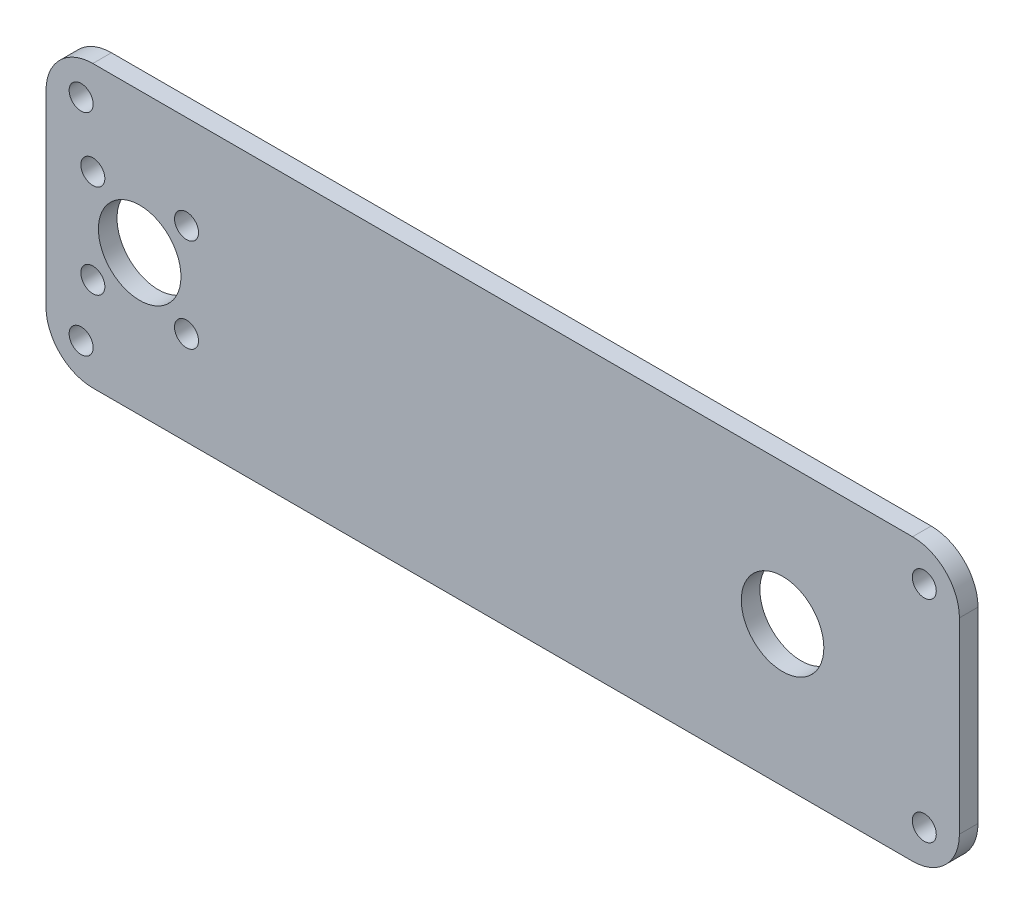
SolidWorks part; units mm, degrees
ref_plane "Front Plane" through (0, 0, 0) normal (0, 0, 1) x (1, 0, 0)
ref_plane "Top Plane" through (0, 0, 0) normal (0, 1, 0) x (1, 0, 0)
ref_plane "Right Plane" through (0, 0, 0) normal (1, 0, 0) x (0, 0, -1)
sketch "Sketch2" plane through (0, 0, 0) normal (0, 0, 1) x (1, 0, 0)
  line L0 (0, 0) -> (0, -72030.4166) construction
  line L1 (78, 24) -> (-78, 24)
  line L2 (78, 24) -> (78, -24)
  line L3 (78, -24) -> (-78, -24)
  line L4 (-78, 24) -> (-78, -24)
  line L5 (78, 24) -> (-78, -24) construction
  line L6 (78, -24) -> (-78, 24) construction
  line L7 (0, 0) -> (72030.4166, 0) construction
  line L9 (-46, 20) -> (17, 20) construction
  line L10 (-46, 20) -> (-46, -20) construction
  line L11 (-46, -20) -> (17, -20) construction
  line L12 (17, 20) -> (17, -20) construction
  line L13 (-46, 20) -> (17, -20) construction
  line L14 (-46, -20) -> (17, 20) construction
  line L15 (-70, 8) -> (-54, 8) construction
  line L16 (-70, 8) -> (-70, -8) construction
  line L17 (-70, -8) -> (-54, -8) construction
  line L18 (-54, 8) -> (-54, -8) construction
  line L19 (-70, 8) -> (-54, -8) construction
  line L20 (-70, -8) -> (-54, 8) construction
  line L21 (10.5, -16) -> (-39.5, -16) construction
  line L22 (10.5, -16) -> (10.5, 16) construction
  line L23 (10.5, 16) -> (-39.5, 16) construction
  line L24 (-39.5, -16) -> (-39.5, 16) construction
  line L25 (10.5, -16) -> (-39.5, 16) construction
  line L26 (10.5, 16) -> (-39.5, -16) construction
  line L31 (7.35, -12) -> (-36.35, -12) construction
  line L32 (7.35, -12) -> (7.35, -8) construction
  line L33 (-50, -12) -> (-74, -12) construction
  line L34 (-50, -12) -> (-50, 12) construction
  line L35 (-50, 12) -> (-74, 12) construction
  line L36 (-74, -12) -> (-74, 12) construction
  line L37 (-50, -12) -> (-74, 12) construction
  line L38 (-50, 12) -> (-74, -12) construction
  line L39 (7.35, 12) -> (-36.35, 12) construction
  line L40 (-36.35, -12) -> (-36.35, -8) construction
  line L41 (7.35, -12) -> (-36.35, 12) construction
  line L42 (7.35, 12) -> (-36.35, -12) construction
  line L44 (-4.7, 19.1) -> (47.7956, 19.1) construction
  line L45 (5.35, -10) -> (-34.35, -10) construction
  line L46 (5.35, -10) -> (5.35, 10) construction
  line L47 (5.35, 10) -> (-34.35, 10) construction
  line L48 (-34.35, -10) -> (-34.35, 10) construction
  line L49 (5.35, -10) -> (-34.35, 10)
  line L50 (5.35, 10) -> (-34.35, -10)
  line L51 (-4.7, -19.1) -> (47.7956, -19.1) construction
  line L52 (-36.35, 8) -> (-42, 8) construction
  line L53 (13, -8) -> (7.35, -8) construction
  line L54 (13, -8) -> (13, 8) construction
  line L55 (13, 8) -> (7.35, 8) construction
  line L56 (-42, -8) -> (-42, 8) construction
  line L57 (13, -8) -> (-42, 8) construction
  line L58 (13, 8) -> (-42, -8) construction
  line L59 (-36.35, -8) -> (-42, -8) construction
  line L60 (-36.35, 8) -> (-36.35, 12) construction
  line L61 (7.35, 8) -> (7.35, 12) construction
  line L64 (9.0311, 16) -> (-48518.2868, 16) construction
  line L65 (10.5, 18.05) -> (13.5, 18.05) construction
  line L66 (10.5, 13.95) -> (13.5, 13.95) construction
  line L67 (-21.5, 13.95) -> (-18.5, 13.95) construction
  line L68 (-21.5, 18.05) -> (-18.5, 18.05) construction
  line L69 (10.5, 13.95) -> (-21.5, 13.95) construction
  line L70 (-21.5, -18.05) -> (-18.5, -18.05) construction
  line L71 (-21.5, -13.95) -> (-18.5, -13.95) construction
  line L72 (10.5, -18.05) -> (13.5, -18.05) construction
  line L73 (10.5, -13.95) -> (13.5, -13.95) construction
  line L75 (72, -18) -> (-72, -18) construction
  line L76 (72, -18) -> (72, 18) construction
  line L77 (72, 18) -> (-72, 18) construction
  line L78 (-72, -18) -> (-72, 18) construction
  line L79 (72, -18) -> (-72, 18) construction
  line L80 (72, 18) -> (-72, -18) construction
  circle A0 centre (-70, 8) radius 2.05
  circle A1 centre (-54, 8) radius 2.05
  circle A2 centre (-54, -8) radius 2.05
  circle A3 centre (-70, -8) radius 2.05
  arc A6 (10.5, 18.05) -> (10.5, 13.95) centre (10.5, 16) ccw construction
  circle A7 centre (-39.5, 16) radius 2.05 construction
  circle A8 centre (-39.5, -16) radius 2.05 construction
  circle A9 centre (-4.7, 0) radius 19.1 construction
  arc A12 (-4.7, 19.1) -> (-4.7, -19.1) centre (-4.7, 0) ccw construction
  circle A13 centre (47.7956, 0) radius 19.1 construction
  arc A14 (47.7956, -19.1) -> (47.7956, 19.1) centre (47.7956, 0) ccw construction
  arc A15 (-4.7, 19.1) -> (-4.7, -19.1) centre (-4.7, 0) ccw construction
  circle A16 centre (47.7956, 0) radius 7.05
  arc A18 (13.5, 13.95) -> (13.5, 18.05) centre (13.5, 16) ccw construction
  arc A19 (-18.5, 13.95) -> (-18.5, 18.05) centre (-18.5, 16) ccw construction
  arc A20 (-21.5, 18.05) -> (-21.5, 13.95) centre (-21.5, 16) ccw construction
  arc A21 (-21.5, -18.05) -> (-21.5, -13.95) centre (-21.5, -16) cw construction
  arc A22 (-18.5, -13.95) -> (-18.5, -18.05) centre (-18.5, -16) cw construction
  arc A23 (10.5, -18.05) -> (10.5, -13.95) centre (10.5, -16) cw construction
  arc A24 (13.5, -13.95) -> (13.5, -18.05) centre (13.5, -16) cw construction
  circle A25 centre (-62, 0) radius 7.05
  circle A26 centre (72, 18) radius 2.05
  circle A27 centre (72, -18) radius 2.05
  circle A28 centre (-72, -18) radius 2.05
  circle A29 centre (-72, 18) radius 2.05
  point P0 (0, 0)
  point P10 (-14.5, 0)
  point P15 (-62, 0)
  point P20 (-14.5, 0)
  point P25 (-14.5, 0)
  point P30 (-62, 0)
  point P39 (-14.5, 0)
  point P47 (-14.5, 0)
  point P52 (-14.5, 0)
  point P95 (0, 0)
  dimension "D7" = 4.1
  dimension "D14" = 38.2
  dimension "D21" = 14.1
  dimension "D1" = 156
  dimension "D2" = 48
  dimension "D3" = 63
  dimension "D4" = 40
  dimension "D5" = 50
  dimension "D6" = 32
  dimension "D8" = 16
  dimension "D9" = 16
  dimension "D10" = 24
  dimension "D11" = 24
  dimension "D12" = 43.7
  dimension "D13" = 24
  dimension "D16" = 39.7
  dimension "D17" = 20
  dimension "D18" = 10.05
  dimension "D19" = 4
  dimension "D20" = 8
  dimension "D22" = 55
  dimension "D23" = 16
  dimension "D24" = 3
  dimension "D26" = 32
  dimension "D27" = 144
  dimension "D28" = 36
  dimension "D25" = 2
extrude "Boss-Extrude2" add sketch "Sketch2" along normal blind 3.175
fillet "Fillet1" radius 8 4 edges at (78, -24, 1.5875) (78, 24, 1.5875) (-78, -24, 1.5875) (-78, 24, 1.5875)
equation "\"w\"= 156mm"
equation "\"h\"= 48mm"
equation "\"servoheight\"= 40mm"
equation "\"servowidth\"= 63mm"
equation "\"servowidthholes\"= 50mm"
equation "\"servoheightholes\"= 32mm"
equation "\"sh\"= 4.1mm"
equation "\"clampHoleSquare\"= 16mm"
equation "\"clampSquare\"= 24mm"
equation "\"D1@Sketch2\"=\"w\""
equation "\"D2@Sketch2\"=\"h\""
equation "\"D3@Sketch2\"=\"servowidth\""
equation "\"D4@Sketch2\"=\"servoheight\""
equation "\"D5@Sketch2\"=\"servowidthholes\""
equation "\"D6@Sketch2\"=\"servoheightholes\""
equation "\"D8@Sketch2\"=\"clampHoleSquare\""
equation "\"D9@Sketch2\"=\"clampHoleSquare\""
equation "\"D10@Sketch2\"=\"clampSquare\""
equation "\"D11@Sketch2\"=\"clampSquare\""
equation "\"D7@Sketch2\"=\"sh\""
equation "\"servoh\"= 20mm"
equation "\"servow\"= 39.7mm"
equation "\"D12@Sketch2\"=\"servow\"+4"
equation "\"D13@Sketch2\"=\"servoh\" +4"
equation "\"pitchDiameter\"= 38.2mm"
equation "\"D14@Sketch2\"=\"pitchDiameter\""
equation "\"D16@Sketch2\"=\"servow\""
equation "\"D17@Sketch2\"=\"servoh\""
equation "\"D18@Sketch2\"=10.05mm"
equation "\"pathLength\"= 225mm"
equation "\"D15@Sketch2\"=\"pathLength\""
equation "\"bearingOD\"= 14.1mm"
equation "\"D21@Sketch2\"=\"bearingOD\""
equation "\"thick\"= 3.175mm"
equation "\"D1@Boss-Extrude2\"=\"thick\""
equation "\"D27@Sketch2\"=\"w\"-12"
equation "\"D28@Sketch2\"=\"h\"-12"
